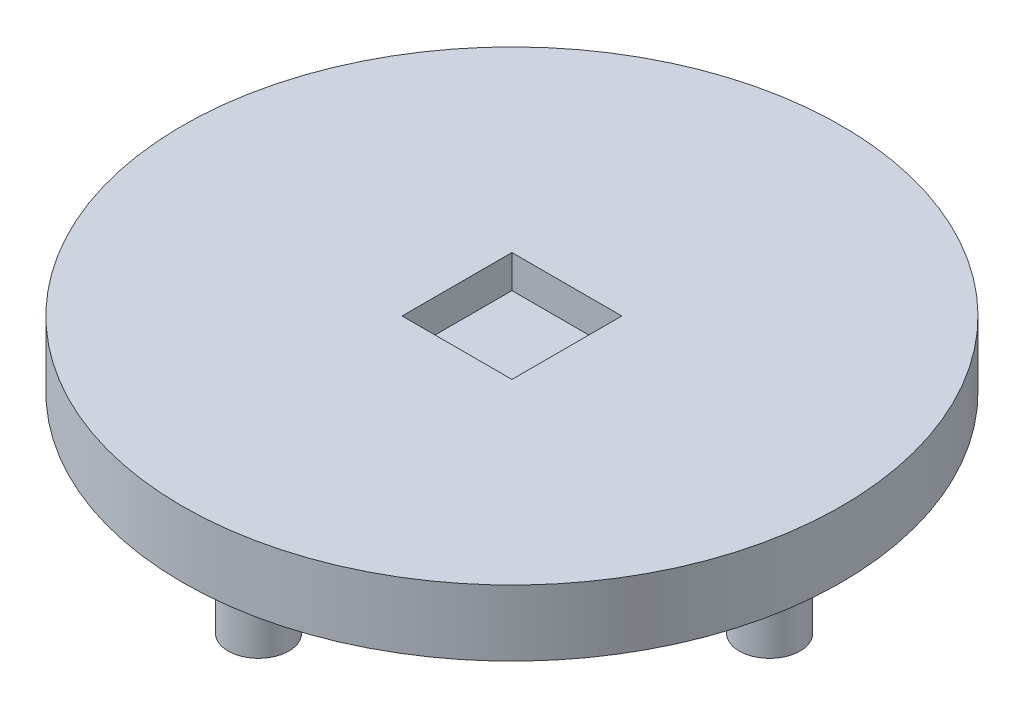
SolidWorks part; units mm, degrees
ref_plane "Front Plane" through (0, 0, 0) normal (0, 0, 1) x (1, 0, 0)
ref_plane "Top Plane" through (0, 0, 0) normal (0, 1, 0) x (1, 0, 0)
ref_plane "Right Plane" through (0, 0, 0) normal (1, 0, 0) x (0, 0, -1)
sketch "Sketch1" plane through (0, 0, 0) normal (0, 1, 0) x (1, 0, 0)
  circle A0 centre (0, 0) radius 30
  dimension "D1" = 60
extrude "Boss-Extrude1" add sketch "Sketch1" along normal blind 6
sketch "Sketch6" plane through (0, 0, -4.1325) normal (0, -1, 0) x (1, 0, 0)
  line L1 (2.0476, 26.5232) -> (-2.0524, 26.5232)
  line L2 (2.0476, 26.5232) -> (2.0476, 27.8732)
  line L3 (2.0476, 27.8732) -> (-2.0524, 27.8732)
  line L4 (-2.0524, 26.5232) -> (-2.0524, 27.8732)
  line L5 (2.0476, 26.5232) -> (-2.0524, 27.8732) construction
  line L6 (2.0476, 27.8732) -> (-2.0524, 26.5232) construction
  line L7 (-0.6774, 29.2482) -> (0.6726, 29.2482)
  line L8 (-0.6774, 29.2482) -> (-0.6774, 25.1482)
  line L9 (-0.6774, 25.1482) -> (0.6726, 25.1482)
  line L10 (0.6726, 29.2482) -> (0.6726, 25.1482)
  line L11 (-0.6774, 29.2482) -> (0.6726, 25.1482) construction
  line L12 (-0.6774, 25.1482) -> (0.6726, 29.2482) construction
  circle A0 centre (-0.0024, 27.1982) radius 2.77
  point P0 (-0.0024, 27.1982)
  point P5 (-0.0024, 27.1982)
  dimension "D5" = 5.54
  dimension "D1" = 1.35
  dimension "D2" = 4.1
  dimension "D3" = 1.35
  dimension "D4" = 4.1
extrude "Boss-Extrude3" add sketch "Sketch6" along normal blind 7.5 contours A0 | L1 L4 L3 L2 | L8 L9 L10 L7
pattern_circular "CirPattern3" count 4 over 360 about axis through (0, 0, -0.1983) along (0, 1, 0) of "Boss-Extrude3"
sketch "Sketch11" plane through (0, 6, 0) normal (0, 1, 0) x (1, 0, 0)
  line L1 (-5, -5) -> (5, -5)
  line L2 (-5, -5) -> (-5, 5)
  line L3 (-5, 5) -> (5, 5)
  line L4 (5, -5) -> (5, 5)
  line L5 (-5, -5) -> (5, 5) construction
  line L6 (-5, 5) -> (5, -5) construction
  point P0 (0, 0)
  dimension "D1" = 10
  dimension "D2" = 10
extrude "Cut-Extrude3" cut sketch "Sketch11" against normal blind 3
